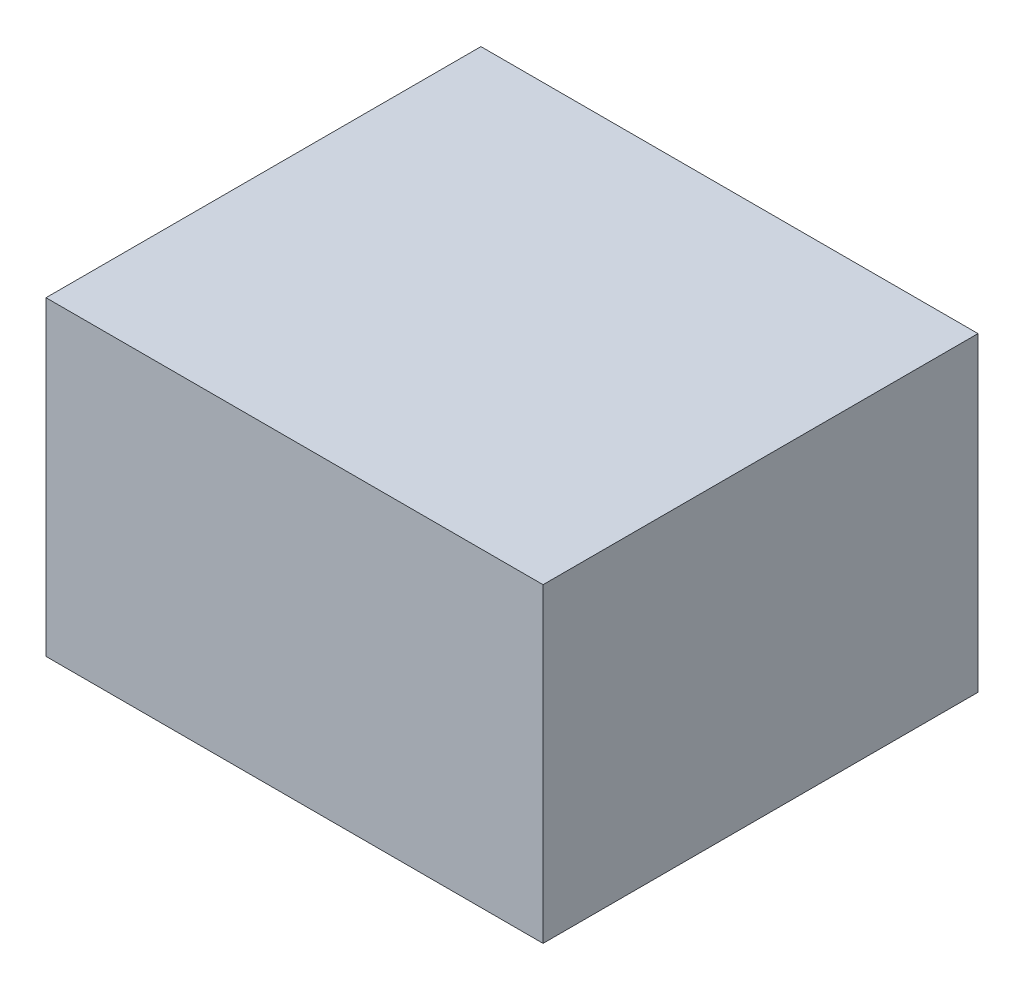
SolidWorks part; units mm, degrees
ref_plane "Front Plane" through (0, 0, 0) normal (0, 0, 1) x (1, 0, 0)
ref_plane "Top Plane" through (0, 0, 0) normal (0, 1, 0) x (1, 0, 0)
ref_plane "Right Plane" through (0, 0, 0) normal (1, 0, 0) x (0, 0, -1)
sketch "Sketch1" plane through (0, 0, 0) normal (0, 0, 1) x (1, 0, 0)
  line L1 (-200, -205) -> (200, -205)
  line L2 (-200, -205) -> (-200, 45)
  line L3 (-200, 45) -> (200, 45)
  line L4 (200, -205) -> (200, 45)
extrude "Boss-Extrude1" add sketch "Sketch1" along normal blind 350 from offset 1815
